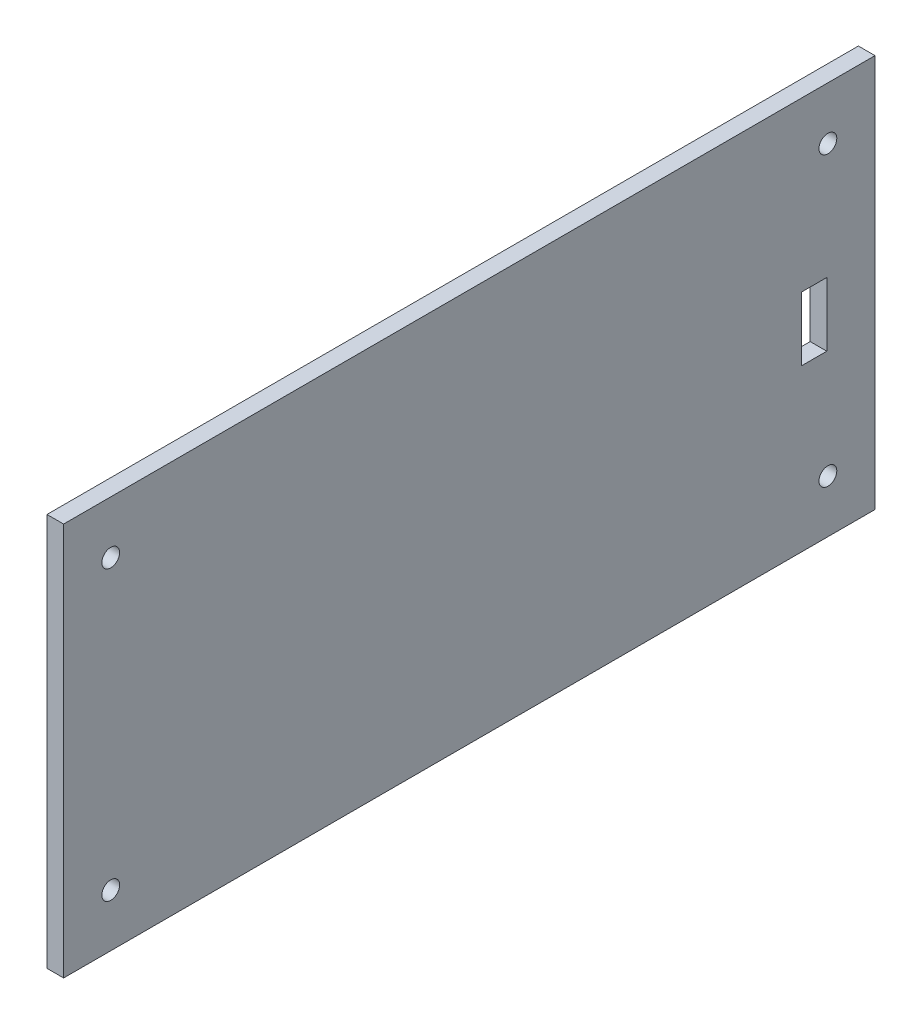
SolidWorks part; units mm, degrees
ref_plane "Front Plane" through (0, 0, 0) normal (0, 0, 1) x (1, 0, 0)
ref_plane "Top Plane" through (0, 0, 0) normal (0, 1, 0) x (1, 0, 0)
ref_plane "Right Plane" through (0, 0, 0) normal (1, 0, 0) x (0, 0, -1)
sketch "Sketch3" plane through (0, 0, 0) normal (1, 0, 0) x (0, 0, -1)
  line L0 (9, 10.05) -> (146, 10.05) construction
  line L1 (0, 0) -> (155, 0)
  line L2 (0, 0) -> (0, 75.1)
  line L3 (0, 75.1) -> (155, 75.1)
  line L4 (155, 0) -> (155, 75.1)
  line L5 (146, 10.05) -> (146, 65.05) construction
  line L6 (146, 65.05) -> (9, 65.05) construction
  line L7 (9, 65.05) -> (9, 10.05) construction
  line L8 (143.3917, 30.8) -> (143.3917, 28.05) construction
  line L9 (140.9917, 30.8) -> (145.7917, 30.8)
  line L10 (140.9917, 30.8) -> (140.9917, 43)
  line L11 (140.9917, 43) -> (145.7917, 43)
  line L12 (145.7917, 30.8) -> (145.7917, 43)
  line L13 (139.2917, 28.05) -> (147.4917, 28.05) construction
  line L14 (138.2917, 36.9) -> (140.9917, 36.9) construction
  line L16 (138.2917, 29.05) -> (138.2917, 44.75) construction
  circle A0 centre (9, 10.05) radius 1.7
  circle A1 centre (146, 10.05) radius 1.7
  circle A2 centre (146, 65.05) radius 1.7
  circle A3 centre (9, 65.05) radius 1.7
  dimension "D7" = 3.4
  dimension "D1" = 10.05
  dimension "D2" = 75.1
  dimension "D3" = 155
  dimension "D4" = 9
  dimension "D5" = 9
  dimension "D6" = 10.05
  dimension "D8" = 4.8
  dimension "D9" = 12.2
extrude "Boss-Extrude1" add sketch "Sketch3" along normal blind 3.175
